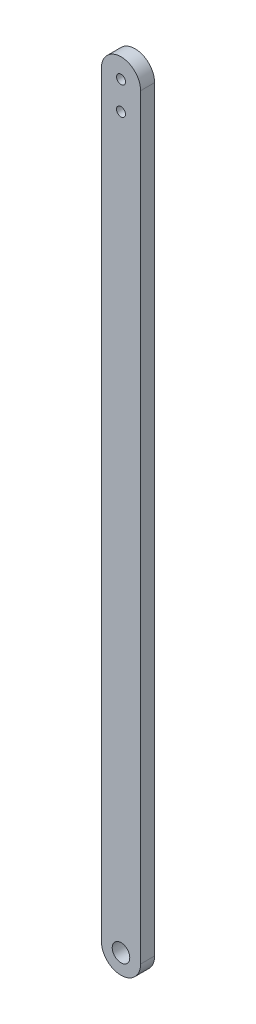
SolidWorks part; units mm, degrees
ref_plane "Front Plane" through (0, 0, 0) normal (0, 0, 1) x (1, 0, 0)
ref_plane "Top Plane" through (0, 0, 0) normal (0, 1, 0) x (1, 0, 0)
ref_plane "Right Plane" through (0, 0, 0) normal (1, 0, 0) x (0, 0, -1)
sketch "Sketch1" plane through (0, 0, 0) normal (0, 0, 1) x (1, 0, 0)
  line L0 (0, 270) -> (0, 0) construction
  line L1 (7, 270) -> (7, 0)
  line L2 (-7, 270) -> (-7, 0)
  arc A1 (7, 270) -> (-7, 270) centre (0, 270) ccw
  circle A2 centre (0, 0) radius 3.1306
  arc A3 (-7, 0) -> (7, 0) centre (0, 0) ccw
  dimension "D1" = 270
  dimension "D3" = 7
  dimension "D2" = 14
extrude "Boss-Extrude1" add sketch "Sketch1" along normal blind 5
sketch "Sketch2" plane through (0, 0, 5) normal (0, 0, 1) x (1, 0, 0)
  line L0 (0, 270) -> (0, 260) construction
  circle A0 centre (0, 270) radius 1.6
  circle A1 centre (0, 260) radius 1.6
extrude "Cut-Extrude1" cut sketch "Sketch2" against normal blind 10
